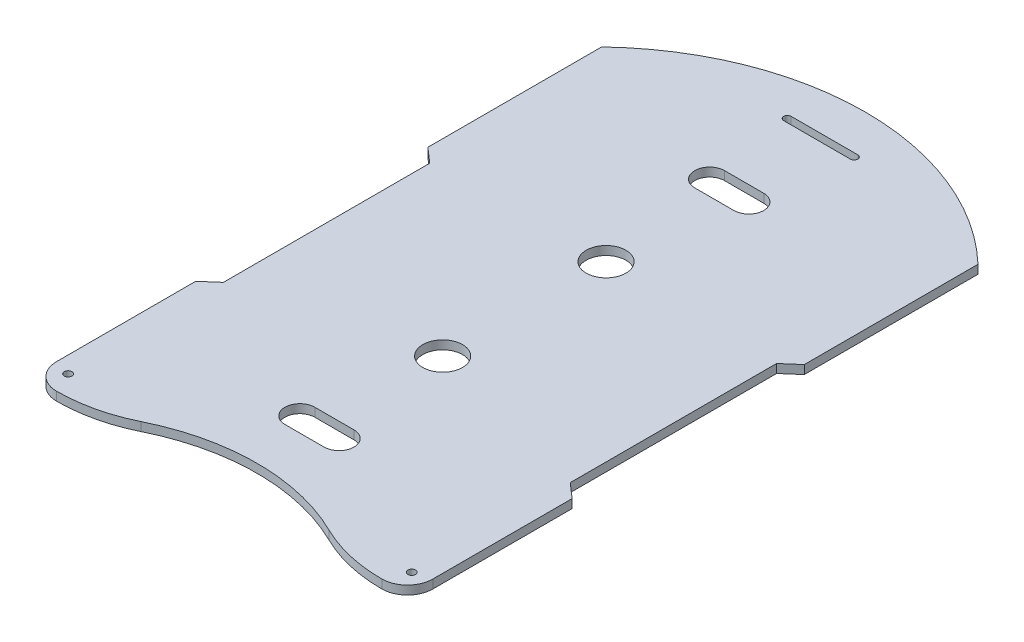
SolidWorks part; units mm, degrees
material "ABS"
ref_plane "Alzado" through (0, 0, 0) normal (0, 0, 1) x (1, 0, 0)
ref_plane "Planta" through (0, 0, 0) normal (0, 1, 0) x (1, 0, 0)
ref_plane "Vista lateral" through (0, 0, 0) normal (1, 0, 0) x (0, 0, -1)
sketch "Croquis1" plane through (0, 0, 0) normal (0, 1, 0) x (1, 0, 0)
  line L0 (0, 0) -> (-69.88, 0) construction
  line L1 (-7.895, -82.555) -> (7.895, -82.555) construction
  line L2 (-7.895, -88.57) -> (7.895, -88.57)
  line L3 (-7.895, -76.54) -> (7.895, -76.54)
  line L5 (0, 137.38) -> (0, -107.7306) construction
  line L6 (0, 24.92) -> (0, -24.96) construction
  line L7 (0, -40.96) -> (0, -76.58) construction
  line L8 (-7.895, 82.555) -> (7.895, 82.555) construction
  line L9 (-7.895, 88.57) -> (7.895, 88.57)
  line L10 (-7.895, 76.54) -> (7.895, 76.54)
  line L11 (0, 40.92) -> (0, 76.54) construction
  line L12 (0, 117.93) -> (0, 88.57) construction
  line L13 (0, 120.93) -> (0, 137.38) construction
  line L17 (-13.415, 119.43) -> (13.415, 119.43) construction
  line L18 (-13.415, 120.93) -> (13.415, 120.93)
  line L19 (-13.415, 117.93) -> (13.415, 117.93)
  line L23 (-75.83, 106.96) -> (-75.83, 36.96)
  line L24 (75.83, 106.96) -> (75.83, 36.96)
  line L28 (75.83, 36.96) -> (69.88, 31.76)
  line L29 (69.88, 31.76) -> (69.88, -51.39)
  line L32 (-69.88, 31.76) -> (-69.88, -51.39)
  line L36 (69.88, -51.39) -> (75.83, -56.59)
  line L39 (-69.88, -51.39) -> (-75.83, -56.59)
  line L47 (75.83, -56.59) -> (75.83, -112.67)
  line L48 (-69.88, 31.76) -> (-75.83, 36.96)
  line L50 (-75.83, -56.59) -> (-75.83, -112.67)
  arc A0 (-7.895, 88.57) -> (-7.895, 76.54) centre (-7.895, 82.555) ccw
  arc A1 (7.895, 76.54) -> (7.895, 88.57) centre (7.895, 82.555) ccw
  circle A2 centre (0, 32.92) radius 8
  arc A3 (-13.415, 120.93) -> (-13.415, 117.93) centre (-13.415, 119.43) ccw
  arc A4 (13.415, 117.93) -> (13.415, 120.93) centre (13.415, 119.43) ccw
  arc A5 (-75.83, 106.96) -> (75.83, 106.96) centre (0, 27.6567) cw
  arc A9 (-37.8413, -116.5308) -> (37.8413, -116.5308) centre (0, -193.4905) cw
  arc A11 (65.53, -122.97) -> (75.83, -112.67) centre (65.53, -112.67) ccw
  arc A12 (-65.53, -122.97) -> (-75.83, -112.67) centre (-65.53, -112.67) cw
  arc A13 (65.53, -122.97) -> (37.8413, -116.5308) centre (65.53, -60.2192) cw
  arc A14 (-65.53, -122.97) -> (-37.8413, -116.5308) centre (-65.53, -60.2192) ccw
  circle A15 centre (69.23, -114.59) radius 1.55
  arc A16 (-7.895, -88.57) -> (-7.895, -76.54) centre (-7.895, -82.555) cw
  arc A17 (7.895, -76.54) -> (7.895, -88.57) centre (7.895, -82.555) cw
  circle A18 centre (0, -32.92) radius 8
  circle A19 centre (-69.23, -114.59) radius 1.55
  point P13 (0, 82.555)
  point P27 (0, 119.43)
  point P35 (0, -82.555)
  point P52 (0, -88.57)
  dimension "D5" = 83.15
  dimension "D6" = 56.08
  dimension "D7" = 5.2
  dimension "D10" = 62.7508
  dimension "D11" = 24.92
  dimension "D12" = 16
  dimension "D14" = 6.015
  dimension "D15" = 19.1606
  dimension "D17" = 29.36
  dimension "D1" = 85.7598
  dimension "D3" = 109.7233
  dimension "D9" = 10.3
  dimension "D18" = 1.5
  dimension "D22" = 3.1
  dimension "D2" = 151.66
  dimension "D4" = 70
  dimension "D8" = 5.95
  dimension "D13" = 15.79
  dimension "D16" = 35.62
  dimension "D19" = 26.83
  dimension "D20" = 16.45
  dimension "D21" = 69.88
  dimension "D23" = 58
  dimension "D24" = 6.6
extrude "Saliente-Extruir1" add sketch "Croquis1" along normal blind 3.5
